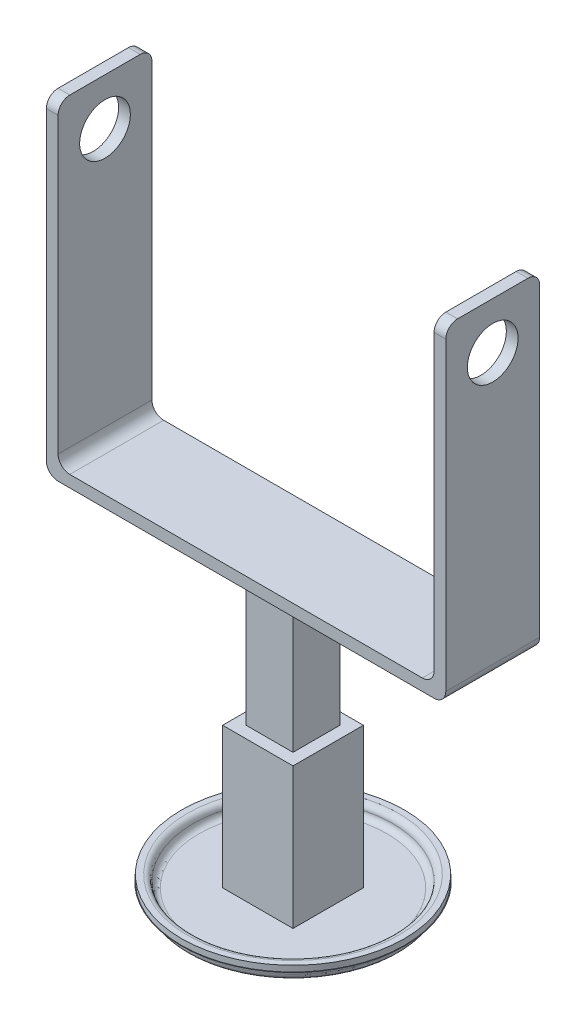
SolidWorks part; units mm, degrees
ref_plane "Front Plane" through (0, 0, 0) normal (0, 0, 1) x (1, 0, 0)
ref_plane "Top Plane" through (0, 0, 0) normal (0, 1, 0) x (1, 0, 0)
ref_plane "Right Plane" through (0, 0, 0) normal (1, 0, 0) x (0, 0, -1)
sketch "Sketch2" plane through (0, 0, 0) normal (0, 0, 1) x (1, 0, 0)
  line L0 (0, 0) -> (54.2617, 0)
  line L2 (60.6117, 6.35) -> (60.325, 6.35)
  line L3 (60.325, 6.35) -> (60.325, 9.525)
  line L4 (60.325, 9.525) -> (57.15, 9.525)
  line L6 (50.8, 3.175) -> (0, 3.175)
  line L7 (0, 3.175) -> (0, 0)
  arc A0 (53.975, 6.35) -> (50.8, 3.175) centre (50.8, 6.35) cw
  arc A1 (57.15, 9.525) -> (53.975, 6.35) centre (57.15, 6.35) ccw
  arc A2 (57.4367, 3.175) -> (60.6117, 6.35) centre (60.6117, 3.175) cw
  arc A3 (54.2617, 0) -> (57.4367, 3.175) centre (54.2617, 3.175) ccw
  point P16 (53.975, 3.175)
  dimension "D3" = 3.175
  dimension "D1" = 50.8
  dimension "D2" = 3.175
  dimension "D4" = 60.325
  dimension "D5" = 3.175
revolve "Revolve1" add sketch "Sketch2" angle 360 about L7
sketch "Sketch3" plane through (0, 3.175, 0) normal (0, 1, 0) x (1, 0, 0)
  line L1 (19.05, 19.05) -> (-19.05, 19.05)
  line L2 (19.05, 19.05) -> (19.05, -19.05)
  line L3 (19.05, -19.05) -> (-19.05, -19.05)
  line L4 (-19.05, 19.05) -> (-19.05, -19.05)
  line L5 (19.05, 19.05) -> (-19.05, -19.05) construction
  line L6 (19.05, -19.05) -> (-19.05, 19.05) construction
  point P0 (0, 0)
  dimension "D1" = 38.1
  dimension "D2" = 38.1
extrude "Boss-Extrude1" add sketch "Sketch3" along normal blind 76.2
sketch "Sketch4" plane through (0, 79.375, 0) normal (0, 1, 0) x (1, 0, 0)
  line L1 (12.7, 12.7) -> (-12.7, 12.7)
  line L2 (12.7, 12.7) -> (12.7, -12.7)
  line L3 (12.7, -12.7) -> (-12.7, -12.7)
  line L4 (-12.7, 12.7) -> (-12.7, -12.7)
  line L5 (12.7, 12.7) -> (-12.7, -12.7) construction
  line L6 (12.7, -12.7) -> (-12.7, 12.7) construction
  point P0 (0, 0)
  dimension "D1" = 25.4
  dimension "D2" = 25.4
extrude "Boss-Extrude2" add sketch "Sketch4" along normal blind 76.2
sketch "Sketch5" plane through (0, 0, 0) normal (0, 0, 1) x (1, 0, 0)
  line L0 (108.077, 155.575) -> (-108.077, 155.575)
  line L1 (12.7, 155.575) -> (-12.7, 155.575) construction
  line L3 (108.077, 155.575) -> (108.077, 333.375)
  line L4 (-108.077, 155.575) -> (-108.077, 333.375)
  line L5 (-108.077, 333.375) -> (-101.727, 333.375)
  line L6 (-101.727, 333.375) -> (-101.727, 161.925)
  line L7 (-101.727, 161.925) -> (101.727, 161.925)
  line L8 (101.727, 161.925) -> (101.727, 333.375)
  line L9 (101.727, 333.375) -> (108.077, 333.375)
  point P3 (-4.8132, 179.0091)
  point P4 (0, 155.575)
  point P6 (-104.902, 333.375)
  point P11 (0, 0)
  point P12 (0, 155.575)
  point P13 (0, 0)
  point P15 (0, 0)
  point P17 (0, 155.575)
  dimension "D1" = 203.454
  dimension "D2" = 6.35
  dimension "D3" = 6.35
  dimension "D4" = 6.35
  dimension "D5" = 177.8
extrude "Boss-Extrude3" add sketch "Sketch5" along normal mid plane 50.8
fillet "Fillet1" radius 6.35 1 edges at (101.727, 161.925, 0)
fillet "Fillet2" radius 6.35 1 edges at (-101.727, 161.925, 0)
fillet "Fillet3" radius 6.35 2 edges at (-108.077, 155.575, 0) (108.077, 155.575, 0)
fillet "Fillet4" radius 6.35 4 edges at (-104.902, 333.375, -25.4) (-104.902, 333.375, 25.4) (104.902, 333.375, 25.4) (104.902, 333.375, -25.4)
sketch "Sketch6" plane through (108.077, 0, 0) normal (1, 0, 0) x (0, 0, -1)
  line L0 (0, 333.375) -> (0, 161.925) construction
  line L1 (-19.05, 333.375) -> (19.05, 333.375) construction
  line L2 (-25.4, 161.925) -> (25.4, 161.925) construction
  line L3 (-87.8855, 307.975) -> (163.148, 307.975) construction
  circle A0 centre (0, 307.975) radius 13.716
  dimension "D2" = 27.432
  dimension "D1" = 25.4
extrude "Cut-Extrude1" cut sketch "Sketch6" against normal through all
